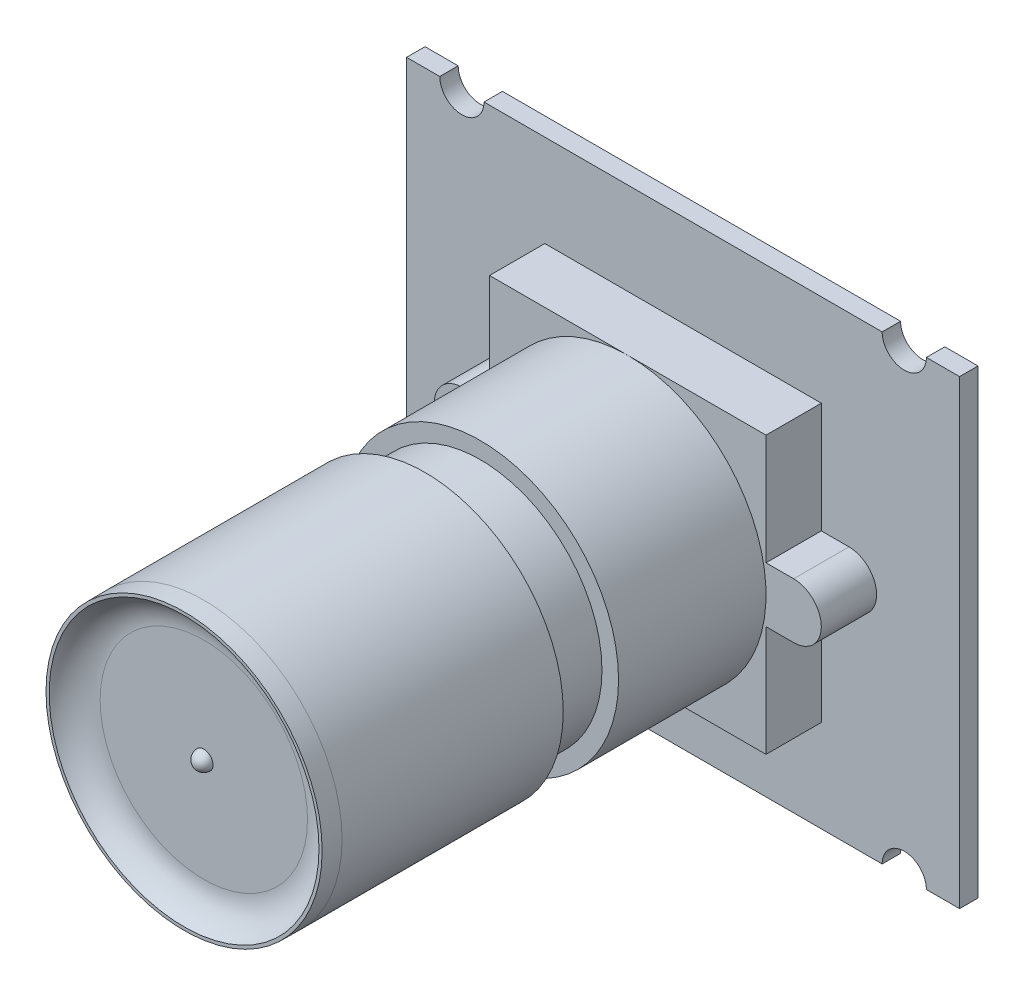
SolidWorks part; units mm, degrees
ref_plane "前视基准面" through (0, 0, 0) normal (0, 0, 1) x (1, 0, 0)
ref_plane "上视基准面" through (0, 0, 0) normal (0, 1, 0) x (1, 0, 0)
ref_plane "右视基准面" through (0, 0, 0) normal (1, 0, 0) x (0, 0, -1)
sketch "草图1" plane through (0, 0, 0) normal (0, 0, 1) x (1, 0, 0)
  line L0 (4.2, 8.956) -> (25.8, 8.956)
  line L1 (0, 8.956) -> (1.8, 8.956)
  line L2 (0, 8.956) -> (0, -16.044)
  line L3 (0, -16.044) -> (1.8, -16.044)
  line L4 (30, 8.956) -> (30, -16.044)
  line L5 (28.2, 8.956) -> (30, 8.956)
  line L6 (4.2, -16.044) -> (25.8, -16.044)
  line L7 (28.2, -16.044) -> (30, -16.044)
  arc A0 (1.8, 8.956) -> (4.2, 8.956) centre (3, 8.956) ccw
  arc A1 (25.8, 8.956) -> (28.2, 8.956) centre (27, 8.956) ccw
  arc A2 (28.2, -16.044) -> (25.8, -16.044) centre (27, -16.044) ccw
  arc A3 (4.2, -16.044) -> (1.8, -16.044) centre (3, -16.044) ccw
  point P12 (0, 0)
  point P13 (0, 0)
  point P14 (0, 0)
  point P15 (0, 0)
  point P16 (0, 0)
  dimension "D1" = 30
  dimension "D3" = 24
  dimension "D4" = 3
  dimension "D2" = 25
extrude "凸台-拉伸1" add sketch "草图1" along normal blind 1
sketch "草图2" plane through (0, 0, 1) normal (0, 0, 1) x (1, 0, 0)
  line L0 (0, 8.956) -> (0, -16.044) construction
  line L1 (30, -16.044) -> (30, 8.956) construction
  line L2 (6, -2.044) -> (24, -2.044)
  line L3 (6, -5.044) -> (24, -5.044)
  line L4 (0, -3.544) -> (30, -3.544) construction
  arc A0 (6, -2.044) -> (6, -5.044) centre (6, -3.544) ccw
  arc A1 (24, -5.044) -> (24, -2.044) centre (24, -3.544) ccw
  point P1 (0, -3.544)
  point P3 (30, -3.544)
  dimension "D1" = 6
  dimension "D2" = 6
extrude "凸台-拉伸2" add sketch "草图2" along normal blind 3
sketch "草图3" plane through (0, 0, 1) normal (0, 0, 1) x (1, 0, 0)
  line L0 (25.8, 8.956) -> (4.2, 8.956) construction
  line L1 (4.2, -16.044) -> (25.8, -16.044) construction
  line L2 (15, 8.956) -> (15, 3.956) construction
  line L3 (15, -11.044) -> (15, -16.044) construction
  line L4 (7.5, 3.956) -> (22.5, 3.956)
  line L5 (7.5, 3.956) -> (7.5, -11.044)
  line L6 (7.5, -11.044) -> (22.5, -11.044)
  line L7 (22.5, 3.956) -> (22.5, -11.044)
  point P0 (15, 8.956)
  point P1 (15, -16.044)
extrude "凸台-拉伸3" add sketch "草图3" along normal blind 3
sketch "草图4" plane through (0, 0, 4) normal (0, 0, 1) x (1, 0, 0)
  line L0 (0, -3.544) -> (30, -3.544) construction
  line L1 (0, 8.956) -> (0, -16.044) construction
  line L2 (30, -16.044) -> (30, 8.956) construction
  circle A0 centre (15, -3.544) radius 7.5
extrude "凸台-拉伸4" add sketch "草图4" along normal blind 8
sketch "草图5" plane through (0, 0, 12) normal (0, 0, 1) x (1, 0, 0)
  line L0 (0, -3.544) -> (30, -3.544) construction
  line L1 (0, 8.956) -> (0, -16.044) construction
  line L2 (30, -16.044) -> (30, 8.956) construction
  circle A0 centre (15, -3.544) radius 6.6
extrude "凸台-拉伸5" add sketch "草图5" along normal blind 3
sketch "草图6" plane through (0, 0, 15) normal (0, 0, 1) x (1, 0, 0)
  line L0 (0, -3.544) -> (30, -3.544) construction
  line L1 (0, 8.956) -> (0, -16.044) construction
  line L2 (30, -16.044) -> (30, 8.956) construction
ref_plane "基准面4" through (0, -3.544, 0) normal (0, -1, 0) x (-1, 0, 0)
sketch "草图7" plane through (0, -3.544, 0) normal (0, -1, 0) x (-1, 0, 0)
  line L0 (0, -15) -> (-30, -15) construction
  line L1 (-15, -15) -> (-7.5, -15)
  line L4 (-7.5, -15) -> (-7.5, -27)
  line L8 (-9.375, -27) -> (-14.5, -27)
  line L9 (-15, -22) -> (-15, -15)
  line L10 (-11.9375, -27) -> (-11.9375, -32.5524) construction
  line L11 (-7.5, -27) -> (-7.5095, -28.0708)
  line L12 (-7.5095, -28.0708) -> (-7.6812, -28.0708)
  line L13 (-15, -22) -> (-15, -27)
  line L14 (-15, -27) -> (-15, -27.5)
  arc A2 (-7.6812, -28.0708) -> (-9.375, -27) centre (-9.375, -28.875) ccw
  arc A4 (-15, -27.5) -> (-14.5, -27) centre (-15, -27) ccw
  dimension "D1" = 7.5
  dimension "D2" = 12
revolve "旋转2" add sketch "草图7" angle 360 about L9
